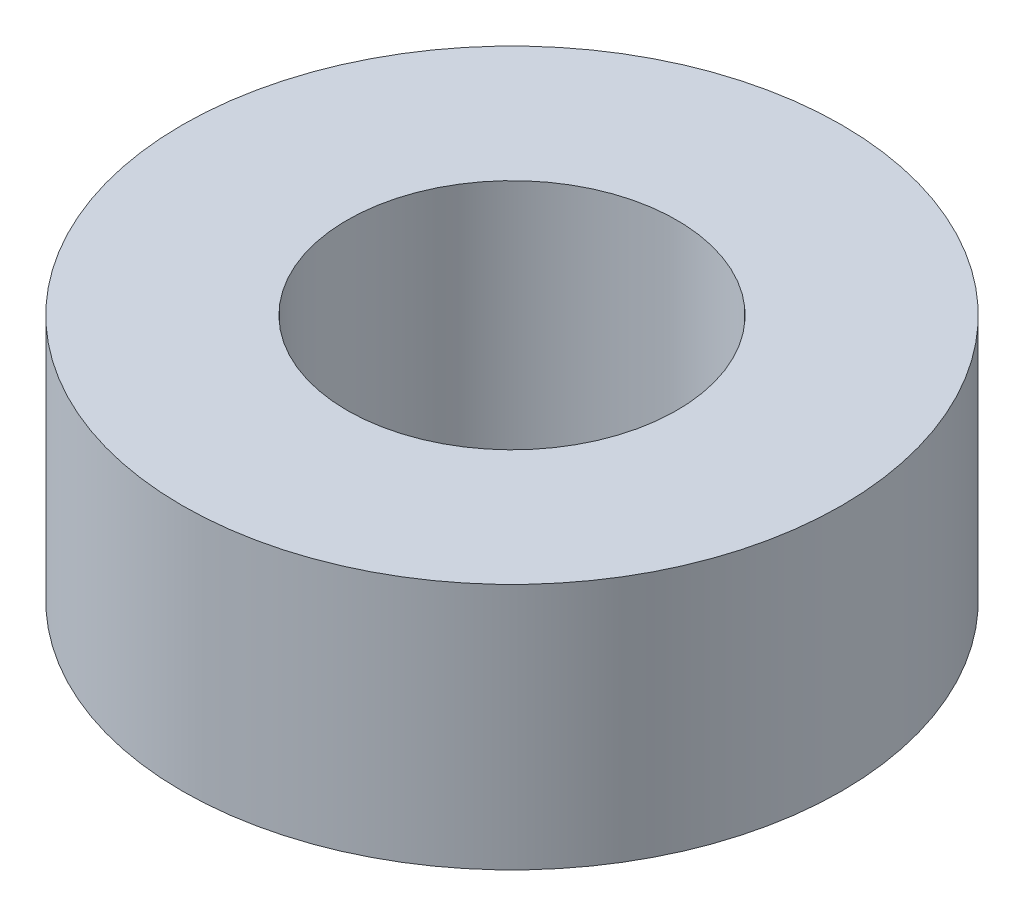
SolidWorks part; units mm, degrees
material "Rubber"
ref_plane "Спереди" through (0, 0, 0) normal (0, 0, 1) x (1, 0, 0)
ref_plane "Сверху" through (0, 0, 0) normal (0, 1, 0) x (1, 0, 0)
ref_plane "Справа" through (0, 0, 0) normal (1, 0, 0) x (0, 0, -1)
sketch "Sketch1" plane through (0, 0, 0) normal (0, 1, 0) x (1, 0, 0)
  circle A0 centre (0, 0) radius 2
  circle A1 centre (0, 0) radius 4
  dimension "D1" = 4
  dimension "D2" = 2
extrude "Boss-Extrude1" add sketch "Sketch1" along normal blind 3
